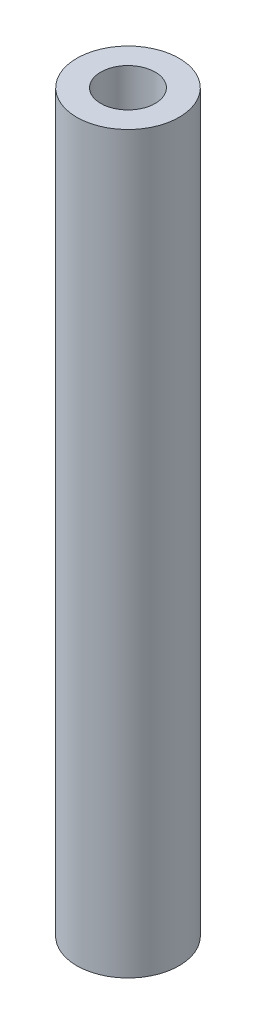
SolidWorks part; units mm, degrees
ref_plane "Front Plane" through (0, 0, 0) normal (0, 0, 1) x (1, 0, 0)
ref_plane "Top Plane" through (0, 0, 0) normal (0, 1, 0) x (1, 0, 0)
ref_plane "Right Plane" through (0, 0, 0) normal (1, 0, 0) x (0, 0, -1)
sketch "Sketch1" plane through (0, 0, 0) normal (0, 1, 0) x (1, 0, 0)
  circle A0 centre (0, 0) radius 9.398
  circle A1 centre (0, 0) radius 5
  dimension "D1" = 18.796
  dimension "D2" = 10
extrude "Boss-Extrude1" add sketch "Sketch1" along normal blind 135
